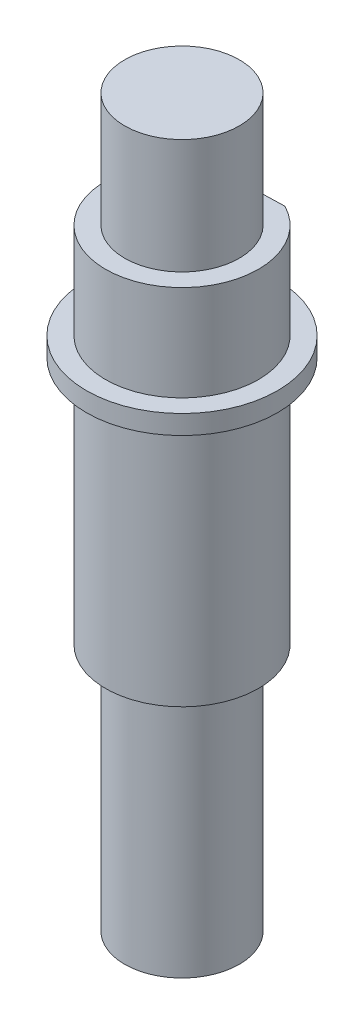
SolidWorks part; units mm, degrees
ref_plane "前视基准面" through (0, 0, 0) normal (0, 0, 1) x (1, 0, 0)
ref_plane "上视基准面" through (0, 0, 0) normal (0, 1, 0) x (1, 0, 0)
ref_plane "右视基准面" through (0, 0, 0) normal (1, 0, 0) x (0, 0, -1)
sketch "草图1" plane through (0, 0, 0) normal (0, 1, 0) x (1, 0, 0)
  circle A0 centre (0, 0) radius 1.5
extrude "凸台-拉伸1" add sketch "草图1" along normal blind 19
ref_plane "基准面1" through (0, 13, 0) normal (0, -1, 0) x (-1, 0, 0)
sketch "草图2" plane through (0, 13, 0) normal (0, -1, 0) x (-1, 0, 0)
  line L0 (0.9119, 1.78) -> (-0.9119, 1.78)
  circle A0 centre (0, 0) radius 1.5
  arc A1 (-0.9119, 1.78) -> (0.9119, 1.78) centre (0, 0) ccw
  dimension "D1" = 1.78
extrude "凸台-拉伸2" add sketch "草图2" along normal blind 6.5
sketch "草图3" plane through (0, 13, 0) normal (0, 1, 0) x (1, 0, 0)
  line L1 (0.9163, 1.7778) -> (-1.0222, 1.719)
  circle A0 centre (0, 0) radius 1.5
  arc A1 (-1.0222, 1.719) -> (0.9163, 1.7778) centre (0, 0) ccw
extrude "凸台-拉伸3" add sketch "草图3" along normal blind 3
sketch "草图4" plane through (0, 13, 0) normal (0, 1, 0) x (1, 0, 0)
  circle A0 centre (0, 0) radius 1.5
  circle A1 centre (0, 0) radius 2.5
extrude "凸台-拉伸4" add sketch "草图4" along normal blind 0.5
